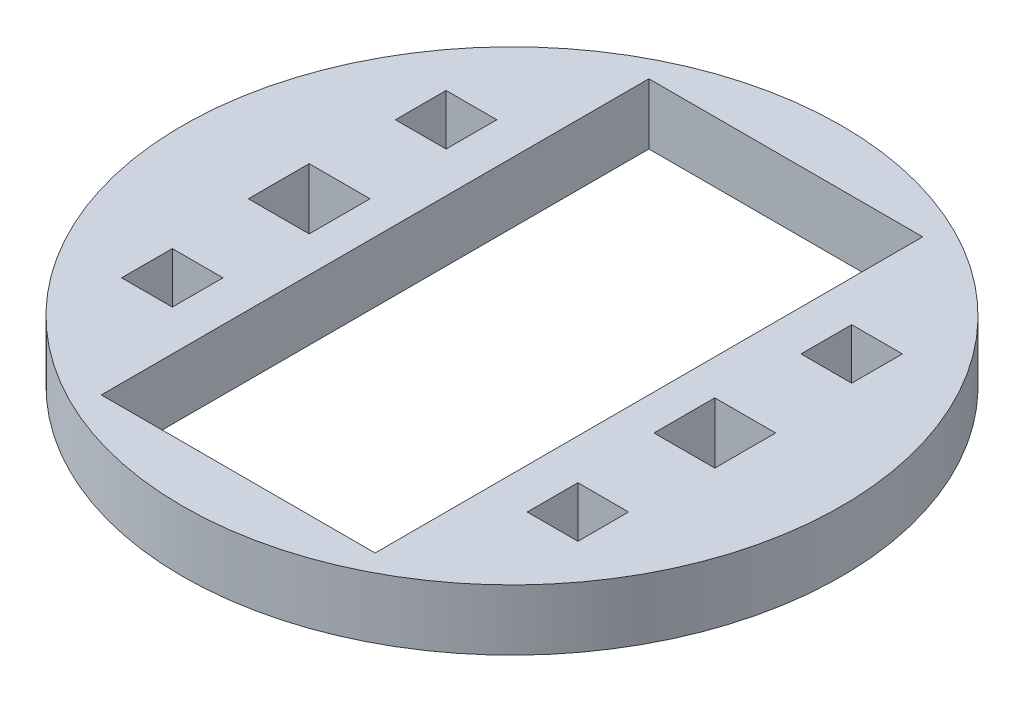
SolidWorks part; units mm, degrees
material "Mahogany"
ref_plane "Front Plane" through (0, 0, 0) normal (0, 0, 1) x (1, 0, 0)
ref_plane "Top Plane" through (0, 0, 0) normal (0, 1, 0) x (1, 0, 0)
ref_plane "Right Plane" through (0, 0, 0) normal (1, 0, 0) x (0, 0, -1)
sketch "Sketch1" plane through (0, 0, 0) normal (0, 1, 0) x (1, 0, 0)
  line L0 (-17, 3) -> (-23, 3)
  line L1 (-13.5, 27) -> (13.5, 27)
  line L2 (-13.5, 27) -> (-13.5, -27)
  line L3 (-13.5, -27) -> (13.5, -27)
  line L4 (13.5, 27) -> (13.5, -27)
  line L5 (-13.5, 27) -> (13.5, -27) construction
  line L6 (-13.5, -27) -> (13.5, 27) construction
  line L7 (-17, 3) -> (-17, -3)
  line L8 (-17, -3) -> (-23, -3)
  line L9 (-23, 3) -> (-23, -3)
  line L10 (-17, 3) -> (-23, -3) construction
  line L11 (-17, -3) -> (-23, 3) construction
  line L12 (17, -3) -> (23, -3)
  line L13 (17, -3) -> (17, 3)
  line L14 (17, 3) -> (23, 3)
  line L15 (23, -3) -> (23, 3)
  line L16 (-20, 0) -> (20, 0) construction
  line L17 (23, 3) -> (17, -3) construction
  line L18 (17, 3) -> (23, -3) construction
  circle A0 centre (0, 0) radius 32.5
  circle A1 centre (0, 0) radius 20 construction
  point P9 (-20, 0)
  point P18 (10.9228, -30.0007)
  point P19 (20, 0)
  dimension "D1" = 65
  dimension "D5" = 40
  dimension "D2" = 54
  dimension "D3" = 27
  dimension "D4" = 6
extrude "Boss-Extrude1" add sketch "Sketch1" along normal blind 6
sketch "Sketch2" plane through (0, 0, 0) normal (0, 1, 0) x (1, 0, 0)
  line L0 (0, 32.5) -> (0, -32.5) construction
  line L1 (17, 3) -> (23, 3) construction
  line L2 (-17.5, 16) -> (-22.5, 16)
  line L3 (-17.5, 16) -> (-17.5, 11)
  line L4 (-17.5, 11) -> (-22.5, 11)
  line L5 (-22.5, 16) -> (-22.5, 11)
  line L10 (-17.5, 16) -> (-22.5, 11) construction
  line L11 (-17.5, 11) -> (-22.5, 16) construction
  line L12 (-17.5, -11) -> (-22.5, -11)
  line L13 (-17.5, -11) -> (-17.5, -16)
  line L14 (-17.5, -16) -> (-22.5, -16)
  line L15 (-22.5, -11) -> (-22.5, -16)
  line L16 (-17.5, -11) -> (-22.5, -16) construction
  line L17 (-17.5, -16) -> (-22.5, -11) construction
  line L18 (22.5, -11) -> (17.5, -11)
  line L19 (22.5, -11) -> (22.5, -16)
  line L20 (22.5, -16) -> (17.5, -16)
  line L21 (17.5, -11) -> (17.5, -16)
  line L22 (22.5, -11) -> (17.5, -16) construction
  line L23 (22.5, -16) -> (17.5, -11) construction
  line L24 (22.5, 16) -> (17.5, 16)
  line L25 (22.5, 16) -> (22.5, 11)
  line L26 (22.5, 11) -> (17.5, 11)
  line L27 (17.5, 16) -> (17.5, 11)
  line L28 (22.5, 16) -> (17.5, 11) construction
  line L29 (22.5, 11) -> (17.5, 16) construction
  line L31 (23, -3) -> (23, 3) construction
  line L32 (-23, 3) -> (-23, -3) construction
  line L33 (-17, -3) -> (-23, -3) construction
  line L34 (17, -3) -> (23, -3) construction
  circle A1 centre (0, 0) radius 32.5 construction
  point P2 (-20, 13.5)
  point P10 (-20, -13.5)
  point P15 (20, -13.5)
  point P18 (20, 13.5)
  point P39 (20, -11)
  dimension "D1" = 8
  dimension "D2" = 8
  dimension "D3" = 5
  dimension "D4" = 5
  dimension "D5" = 5
  dimension "D6" = 5
extrude "Cut-Extrude2" cut sketch "Sketch2" against normal through all and the other way through all
